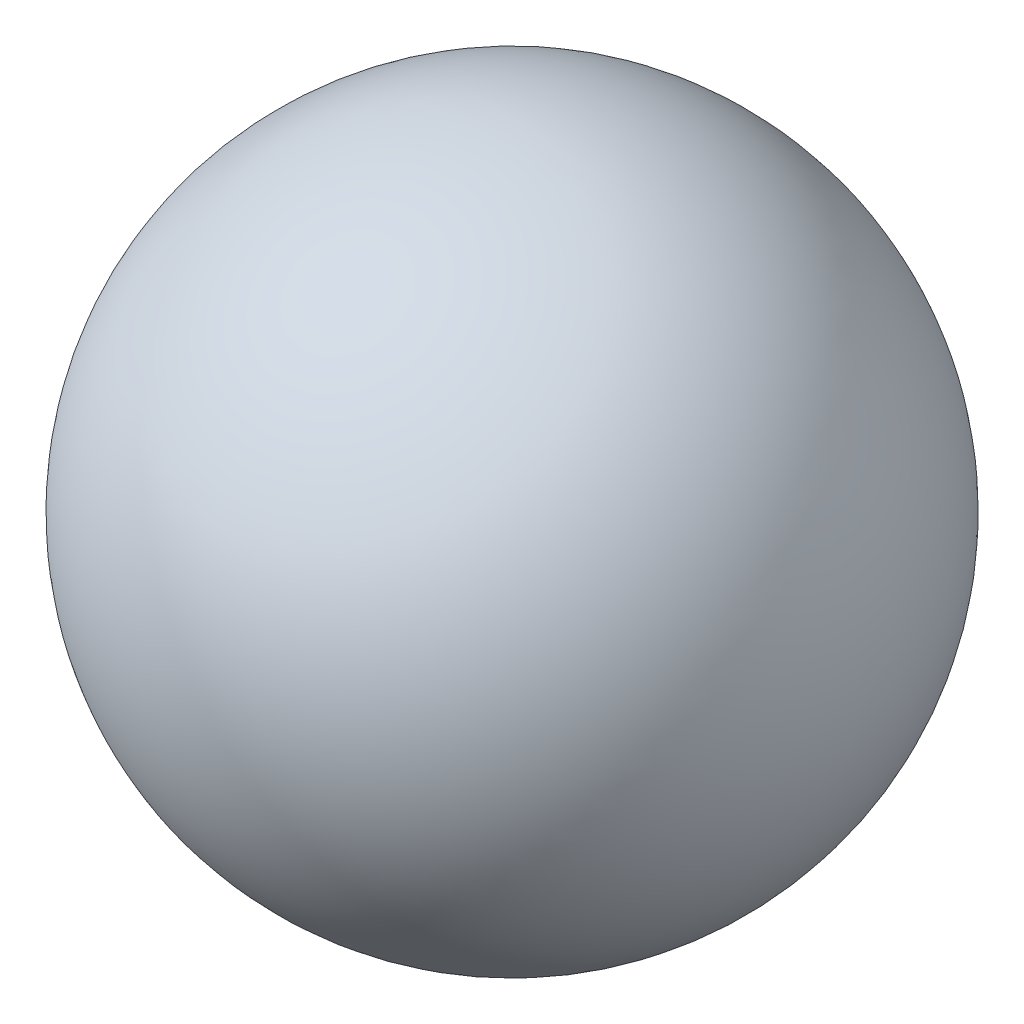
SolidWorks part; units mm, degrees
material "Acrylic (Medium-high impact)"
ref_plane "Front" through (0, 0, 0) normal (0, 0, 1) x (1, 0, 0)
ref_plane "Top" through (0, 0, 0) normal (0, 1, 0) x (1, 0, 0)
ref_plane "Right" through (0, 0, 0) normal (1, 0, 0) x (0, 0, -1)
sketch "Sketch1" plane through (0, 0, 0) normal (0, 1, 0) x (1, 0, 0)
  line L0 (0, -46) -> (0, 46)
  arc A0 (0, 46) -> (0, -46) centre (0, 0) ccw
  dimension "D1" = 92
revolve "Revolve2" add sketch "Sketch1" angle 360 about L0
shell "Shell1" thickness 2.5
